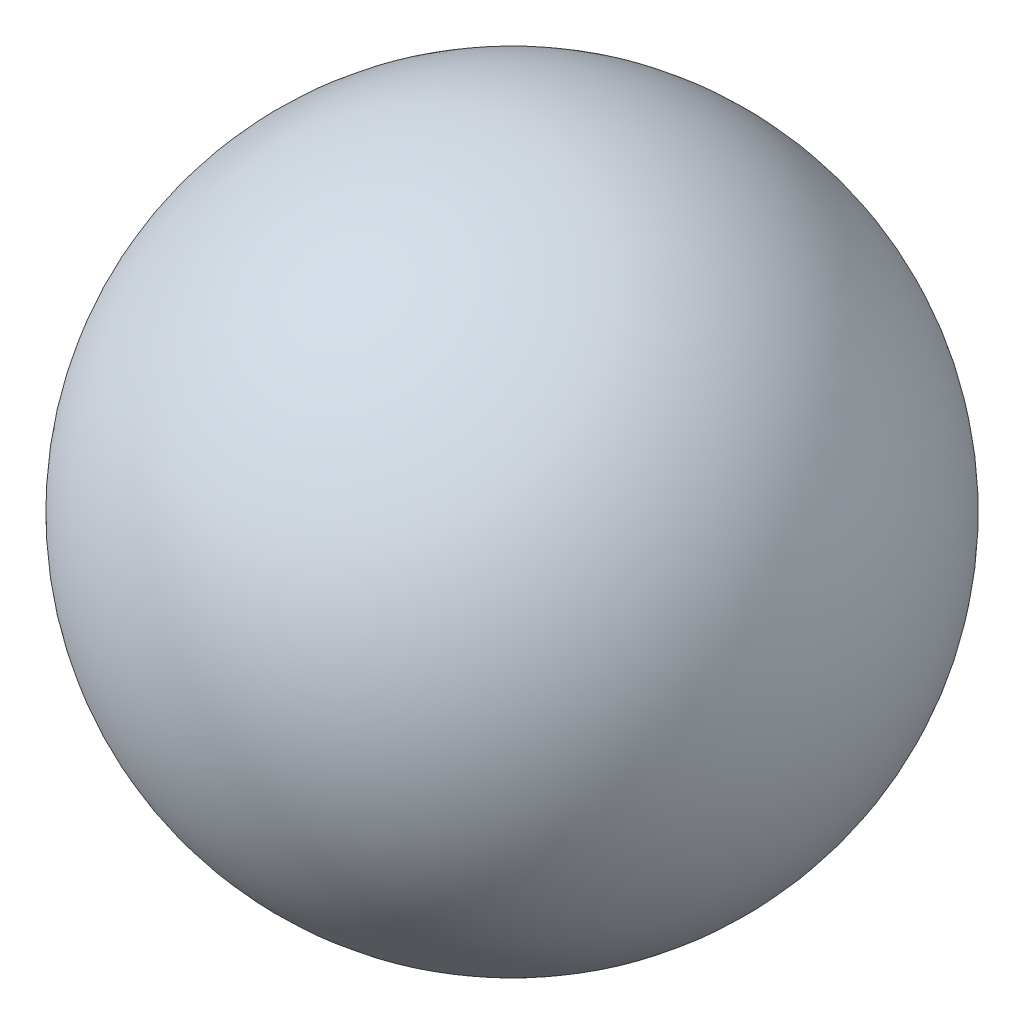
SolidWorks part; units mm, degrees
ref_plane "Front Plane" through (0, 0, 0) normal (0, 0, 1) x (1, 0, 0)
ref_plane "Top Plane" through (0, 0, 0) normal (0, 1, 0) x (1, 0, 0)
ref_plane "Right Plane" through (0, 0, 0) normal (1, 0, 0) x (0, 0, -1)
sketch "Sketch1" plane through (0, 0, 0) normal (0, 0, 1) x (1, 0, 0)
  line L0 (0, 2.3584) -> (0, 0)
  arc A0 (0, 0) -> (0, 2.3584) centre (0, 1.1792) cw
  dimension "D1" = 1.1792
revolve "Revolve1" add sketch "Sketch1" angle 360 about L0
